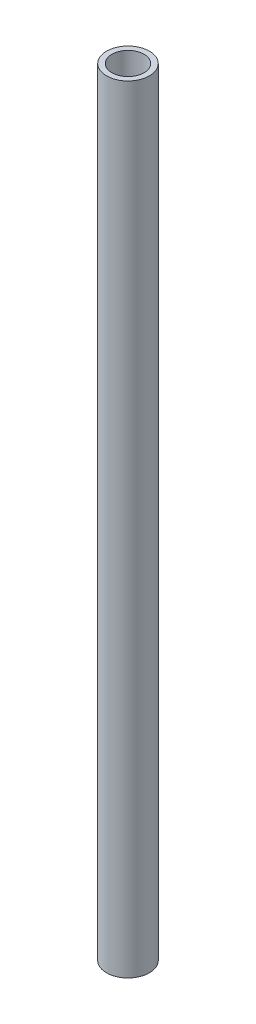
SolidWorks part; units mm, degrees
material "Copper"
ref_plane "Front Plane" through (0, 0, 0) normal (0, 0, 1) x (1, 0, 0)
ref_plane "Top Plane" through (0, 0, 0) normal (0, 1, 0) x (1, 0, 0)
ref_plane "Right Plane" through (0, 0, 0) normal (1, 0, 0) x (0, 0, -1)
sketch "Sketch1" plane through (0, 0, 0) normal (0, 1, 0) x (1, 0, 0)
  circle A0 centre (0, 0) radius 4
  circle A1 centre (0, 0) radius 3
  dimension "D1" = 6
  dimension "D2" = 8
extrude "Boss-Extrude1" add sketch "Sketch1" along normal blind 145
